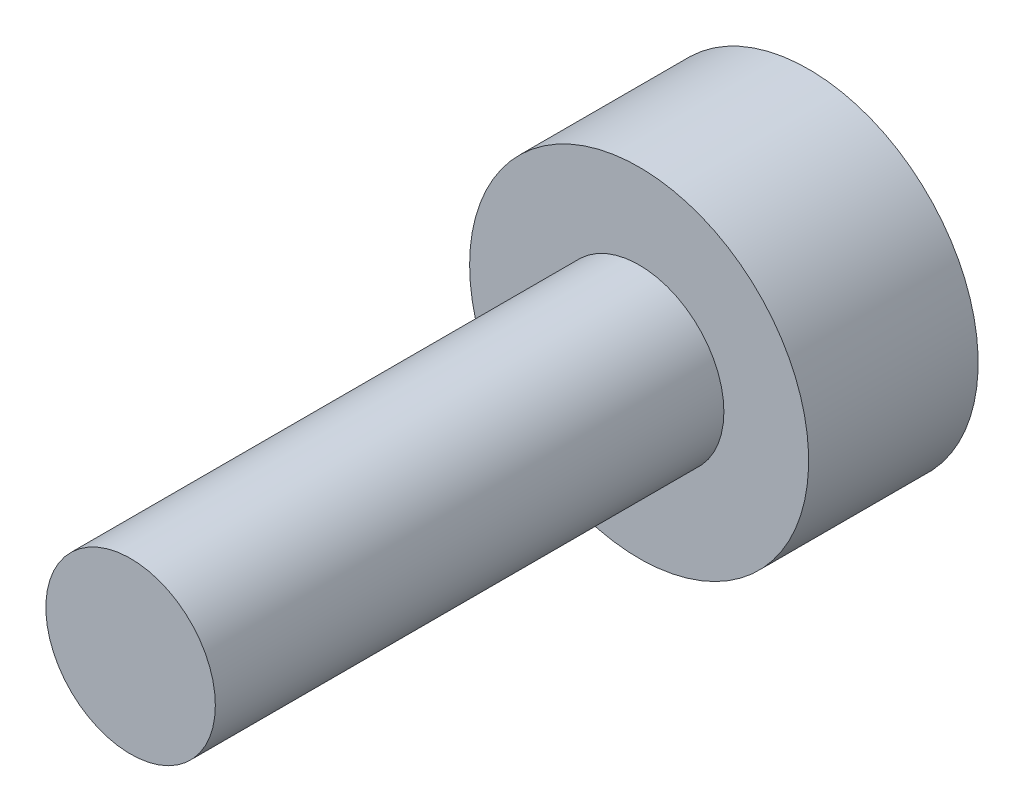
SolidWorks part; units mm, degrees
ref_plane "前视基准面" through (0, 0, 0) normal (0, 0, 1) x (1, 0, 0)
ref_plane "上视基准面" through (0, 0, 0) normal (0, 1, 0) x (1, 0, 0)
ref_plane "右视基准面" through (0, 0, 0) normal (1, 0, 0) x (0, 0, -1)
sketch "草图1" plane through (0, 0, 0) normal (0, 0, 1) x (1, 0, 0)
  circle A0 centre (0, 0) radius 1
extrude "凸台-拉伸1" add sketch "草图1" along normal blind 6
sketch "草图2" plane through (0, 0, 0) normal (0, 0, -1) x (-1, 0, 0)
  circle A0 centre (0, 0) radius 2
extrude "凸台-拉伸2" add sketch "草图2" along normal blind 2
sketch "草图3" plane through (0, 0, -2) normal (0, 0, -1) x (-1, 0, 0)
  line L1 (1, 0) -> (0.5, 0.866)
  line L2 (0.5, 0.866) -> (-0.5, 0.866)
  line L3 (-0.5, 0.866) -> (-1, 0)
  line L4 (-1, 0) -> (-0.5, -0.866)
  line L5 (-0.5, -0.866) -> (0.5, -0.866)
  line L6 (0.5, -0.866) -> (1, 0)
  circle A0 centre (0, 0) radius 1 construction
extrude "切除-拉伸1" cut sketch "草图3" against normal blind 1
